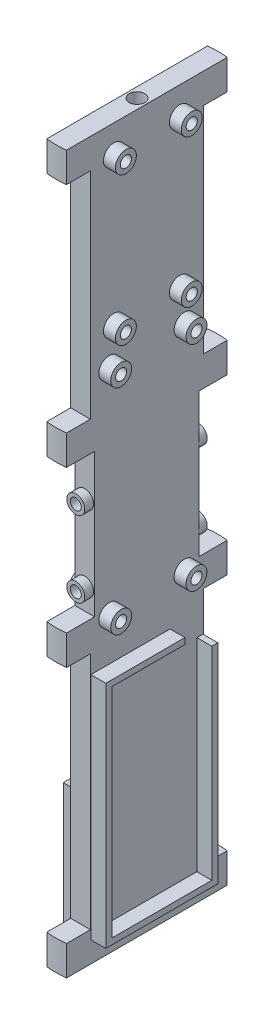
SolidWorks part; units mm, degrees
ref_plane "Front Plane" through (0, 0, 0) normal (0, 0, 1) x (1, 0, 0)
ref_plane "Top Plane" through (0, 0, 0) normal (0, 1, 0) x (1, 0, 0)
ref_plane "Right Plane" through (0, 0, 0) normal (1, 0, 0) x (0, 0, -1)
sketch "Sketch1" plane through (0, 0, 0) normal (0, 1, 0) x (1, 0, 0)
  line L2 (2.0955, -17.0804) -> (2.0955, 17.0804)
  line L4 (-2.0955, -17.0804) -> (-2.0955, 17.0804)
  line L5 (2.0955, -17.0804) -> (-2.0955, 17.0804) construction
  line L6 (2.0955, 17.0804) -> (-2.0955, -17.0804) construction
  circle A0 centre (0, 0) radius 17.4625 construction
  arc A1 (-2.0955, 17.0804) -> (2.0955, 17.0804) centre (0, 0) cw
  arc A2 (-2.0955, -17.0804) -> (2.0955, -17.0804) centre (0, 0) ccw
  circle A4 centre (0, 0) radius 1.651
  point P11 (0, 0)
  dimension "D1" = 34.925
  dimension "D2" = 4.191
  dimension "D3" = 0.254
  dimension "D5" = 3.302
extrude "Boss-Extrude1" add sketch "Sketch1" along normal blind 152.4
ref_plane "Plane1" through (0, 0, -17.2085) normal (0, 0, -1) x (-1, 0, 0)
sketch "Sketch2" plane through (0, 0, -17.2085) normal (0, 0, -1) x (-1, 0, 0)
  line L0 (-2.0955, 152.4) -> (-2.0955, 0) construction
  line L1 (-2.0955, 93.98) -> (2.0955, 93.98)
  line L2 (-2.0955, 93.98) -> (-2.0955, 63.5)
  line L3 (-2.0955, 63.5) -> (2.0955, 63.5)
  line L4 (2.0955, 93.98) -> (2.0955, 63.5)
  line L5 (2.0955, 152.4) -> (2.0955, 0) construction
  line L6 (0, 0) -> (0, 152.4) construction
  line L7 (2.0955, 152.4) -> (-2.0955, 152.4) construction
  point P6 (0, 76.2)
  dimension "D1" = 12.7
  dimension "D2" = 30.48
extrude "Cut-Extrude1" cut sketch "Sketch2" against normal blind 6.096
sketch "Sketch3" plane through (0, 0, -11.1125) normal (0, 0, -1) x (-1, 0, 0)
  line L0 (0, 63.5) -> (0, 93.98) construction
  line L1 (2.0955, 63.5) -> (-2.0955, 63.5) construction
  line L2 (-2.0955, 93.98) -> (2.0955, 93.98) construction
  line L3 (-2.0955, 63.5) -> (2.0955, 63.5) construction
  circle A0 centre (0, 68.0339) radius 1.905
  circle A1 centre (0, 84.1629) radius 1.905
  dimension "D1" = 3.81
  dimension "D3" = 16.129
  dimension "D4" = 4.5339
extrude "Boss-Extrude2" add sketch "Sketch3" along normal blind 1.905
sketch "Sketch4" plane through (0, 0, -13.0175) normal (0, 0, -1) x (-1, 0, 0)
  circle A0 centre (0, 84.1629) radius 1.1748
  circle A1 centre (0, 68.0339) radius 1.1748
  dimension "D1" = 2.3495
extrude "Cut-Extrude2" cut sketch "Sketch4" against normal blind 6.35
mirror "Mirror1" about plane through (0, 0, 0) normal (0, 0, 1) of "Cut-Extrude2", "Boss-Extrude2", "Cut-Extrude1"
sketch "Sketch5" plane through (-2.0955, 0, 0) normal (-1, 0, 0) x (0, 0, 1)
  line L0 (-17.0804, 152.4) -> (17.0804, 152.4) construction
  line L10 (8.385, 150.495) -> (8.385, 106.045)
  line L11 (8.385, 106.045) -> (10.29, 106.045)
  line L12 (10.29, 150.495) -> (10.29, 106.045)
  line L14 (-8.385, 150.495) -> (-8.385, 106.045)
  line L15 (-8.385, 106.045) -> (-10.29, 106.045)
  line L16 (-10.29, 150.495) -> (-10.29, 106.045)
  line L17 (-7.75, 149.86) -> (-7.75, 82.86) construction
  line L18 (7.75, 149.86) -> (7.75, 82.86) construction
  line L19 (-8.385, 150.495) -> (8.385, 150.495)
  line L20 (10.29, 150.495) -> (10.29, 152.4)
  line L21 (10.29, 152.4) -> (-10.29, 152.4)
  line L22 (-10.29, 152.4) -> (-10.29, 150.495)
  dimension "D1" = 46.355
  dimension "D2" = 1.905
  dimension "D3" = 1.905
  dimension "D4" = 0.635
  dimension "D5" = 0.635
extrude "2s LiPo Mounting Frame 550 mAh" [suppressed] add sketch "Sketch5" along normal blind 6.35
sketch "Sketch10" plane through (2.0955, 0, 0) normal (1, 0, 0) x (0, 0, -1)
  line L4 (10.405, 0.635) -> (10.405, 35.445)
  line L5 (10.405, 35.445) -> (-2.785, 35.445)
  line L6 (-10.405, 35.445) -> (-10.405, 0.635)
  line L7 (-10.405, 0.635) -> (10.405, 0.635)
  line L12 (9.135, 34.175) -> (-2.785, 34.175)
  line L13 (-9.135, 34.175) -> (-9.135, 1.905)
  line L14 (-9.135, 1.905) -> (9.135, 1.905)
  line L15 (9.135, 1.905) -> (9.135, 34.175)
  line L16 (-9.135, 34.175) -> (-9.135, 35.445)
  line L17 (-2.785, 34.175) -> (-2.785, 35.445)
  line L18 (-9.135, 35.445) -> (-10.405, 35.445)
  line L19 (10.405, 35.445) -> (-10.405, 35.445) construction
  line L20 (9.135, 34.175) -> (-9.135, 34.175) construction
  dimension "D3" = 6.35
  dimension "D2" = 1.27
extrude "1s Lipo Mounting Frame 550 mAh" [suppressed] add sketch "Sketch10" along normal blind 2.54
sketch "Sketch11" plane through (-2.0955, 0, 0) normal (-1, 0, 0) x (0, 0, 1)
  line L0 (-7.75, 149.86) -> (-7.75, 82.86) construction
  line L1 (-7.75, 82.225) -> (7.75, 82.225)
  line L2 (-7.75, 82.225) -> (-7.75, 80.32)
  line L3 (-7.75, 80.32) -> (7.75, 80.32)
  line L4 (7.75, 82.225) -> (7.75, 80.32)
  line L5 (7.75, 149.86) -> (7.75, 82.86) construction
  dimension "D1" = 0.635
  dimension "D2" = 1.905
extrude "2s LiPo Mounting Stop" [suppressed] add sketch "Sketch11" along normal blind 1.905
sketch "Sketch6" plane through (-2.0955, 0, 0) normal (-1, 0, 0) x (0, 0, 1)
  circle A0 centre (-3.1115, 52.5145) radius 2.2225
  arc A1 (11.049, 12.2555) -> (7.874, 12.2555) centre (9.4615, 12.2555) ccw construction
  arc A2 (-4.699, 52.5145) -> (-1.524, 52.5145) centre (-3.1115, 52.5145) ccw construction
  arc A3 (-1.524, 52.5145) -> (-4.699, 52.5145) centre (-3.1115, 52.5145) ccw construction
  arc A4 (11.049, 12.2555) -> (7.874, 12.2555) centre (9.4615, 12.2555) ccw construction
  arc A5 (-4.699, 52.5145) -> (-1.524, 52.5145) centre (-3.1115, 52.5145) ccw construction
  arc A6 (-1.524, 52.5145) -> (-4.699, 52.5145) centre (-3.1115, 52.5145) ccw construction
  arc A7 (7.874, 12.2555) -> (11.049, 12.2555) centre (9.4615, 12.2555) ccw construction
  arc A8 (7.874, 12.2555) -> (11.049, 12.2555) centre (9.4615, 12.2555) ccw construction
  circle A9 centre (-3.1115, 52.5145) radius 1.1811
  circle A10 centre (9.4615, 12.2555) radius 2.2225
  circle A11 centre (9.4615, 12.2555) radius 1.1811
  dimension "D1" = 2.3622
  dimension "D2" = 4.445
extrude "Eggfinder Mini Mounts 550 mAh" [suppressed] add sketch "Sketch6" along normal up to surface (4.064 mm away)
sketch "Sketch7" plane through (2.0955, 0, 0) normal (1, 0, 0) x (0, 0, -1)
  circle A0 centre (8.001, 107.823) radius 1.3716 construction
  circle A1 centre (-8.001, 107.823) radius 1.3716 construction
  circle A2 centre (-8.001, 62.357) radius 1.3716 construction
  circle A3 centre (8.001, 62.357) radius 1.3716 construction
  circle A4 centre (8.001, 107.823) radius 1.3716 construction
  circle A5 centre (-8.001, 107.823) radius 1.3716 construction
  circle A6 centre (-8.001, 62.357) radius 1.3716 construction
  circle A7 centre (8.001, 62.357) radius 1.3716 construction
  circle A8 centre (8.001, 62.357) radius 2.2225
  circle A9 centre (8.001, 62.357) radius 1.1811
  circle A10 centre (-8.001, 62.357) radius 2.2225
  circle A11 centre (-8.001, 62.357) radius 1.1811
  circle A12 centre (-8.001, 107.823) radius 2.2225
  circle A13 centre (-8.001, 107.823) radius 1.1811
  circle A14 centre (8.001, 107.823) radius 2.2225
  circle A15 centre (8.001, 107.823) radius 1.1811
  dimension "D1" = 2.3622
  dimension "D2" = 4.445
extrude "Stratologger Mounts" add sketch "Sketch7" along normal up to surface (2.54 mm away)
sketch "Sketch8" plane through (2.0955, 0, 0) normal (1, 0, 0) x (0, 0, -1)
  circle A0 centre (7, 146.51) radius 1.65 construction
  circle A1 centre (-7, 146.51) radius 1.65 construction
  circle A2 centre (-7, 115.11) radius 1.65 construction
  circle A3 centre (7, 115.11) radius 1.65 construction
  circle A4 centre (7, 146.51) radius 1.65 construction
  circle A5 centre (-7, 146.51) radius 1.65 construction
  circle A6 centre (-7, 115.11) radius 1.65 construction
  circle A7 centre (7, 115.11) radius 1.65 construction
  circle A8 centre (7, 115.11) radius 2.2225
  circle A9 centre (7, 115.11) radius 1.1811
  circle A10 centre (-7, 115.11) radius 2.2225
  circle A11 centre (-7, 115.11) radius 1.1811
  circle A12 centre (-7, 146.51) radius 1.1811
  circle A13 centre (-7, 146.51) radius 2.2225
  circle A14 centre (7, 146.51) radius 1.1811
  circle A15 centre (7, 146.51) radius 2.2225
  dimension "D1" = 2.3622
  dimension "D2" = 4.445
extrude "EasyMini Mounts" add sketch "Sketch8" along normal up to surface (2.54 mm away)
sketch "Sketch9" plane through (2.0955, 0, 0) normal (1, 0, 0) x (0, 0, -1)
  line L0 (-17.0804, 63.5) -> (-17.0804, 0) construction
  line L1 (19.6204, 6.35) -> (12.0004, 6.35)
  line L2 (19.6204, 6.35) -> (19.6204, 57.15)
  line L3 (19.6204, 57.15) -> (12.0004, 57.15)
  line L4 (12.0004, 6.35) -> (12.0004, 57.15)
  line L5 (-17.0804, 152.4) -> (-17.0804, 93.98) construction
  line L6 (-19.6204, 6.35) -> (-12.0004, 6.35)
  line L7 (-19.6204, 6.35) -> (-19.6204, 57.15)
  line L8 (-19.6204, 57.15) -> (-12.0004, 57.15)
  line L9 (-12.0004, 6.35) -> (-12.0004, 57.15)
  line L11 (-19.6204, 100.33) -> (-12.0004, 100.33)
  line L12 (-19.6204, 100.33) -> (-19.6204, 146.05)
  line L13 (-19.6204, 146.05) -> (-12.0004, 146.05)
  line L14 (-12.0004, 100.33) -> (-12.0004, 146.05)
  line L16 (19.6204, 100.33) -> (12.0004, 100.33)
  line L17 (19.6204, 100.33) -> (19.6204, 146.05)
  line L18 (19.6204, 146.05) -> (12.0004, 146.05)
  line L19 (12.0004, 100.33) -> (12.0004, 146.05)
  line L20 (-17.0804, 152.4) -> (17.0804, 152.4) construction
  line L21 (-11.1125, 93.98) -> (-17.0804, 93.98) construction
  line L22 (-11.1125, 63.5) -> (-17.0804, 63.5) construction
  line L23 (-17.0804, 0) -> (17.0804, 0) construction
  line L24 (17.0804, 63.5) -> (17.0804, 0) construction
  dimension "D1" = 5.08
  dimension "D2" = 6.35
  dimension "D3" = 6.35
  dimension "D4" = 6.35
  dimension "D5" = 6.35
  dimension "D6" = 2.54
  dimension "D7" = 2.54
  dimension "D8" = 2.54
extrude "Wire Passthroughs" cut sketch "Sketch9" against normal through all
sketch "Sketch12" plane through (-2.0955, 0, 0) normal (-1, 0, 0) x (0, 0, 1)
  arc A1 (-7.874, 103.9495) -> (-4.699, 103.9495) centre (-6.2865, 103.9495) ccw construction
  arc A2 (-4.699, 103.9495) -> (-7.874, 103.9495) centre (-6.2865, 103.9495) ccw construction
  arc A3 (4.699, 63.6905) -> (7.874, 63.6905) centre (6.2865, 63.6905) ccw construction
  arc A4 (7.874, 63.6905) -> (4.699, 63.6905) centre (6.2865, 63.6905) ccw construction
  arc A5 (-7.874, 103.9495) -> (-4.699, 103.9495) centre (-6.2865, 103.9495) ccw construction
  arc A6 (-4.699, 103.9495) -> (-7.874, 103.9495) centre (-6.2865, 103.9495) ccw construction
  arc A7 (4.699, 63.6905) -> (7.874, 63.6905) centre (6.2865, 63.6905) ccw construction
  arc A8 (7.874, 63.6905) -> (4.699, 63.6905) centre (6.2865, 63.6905) ccw construction
  circle A9 centre (-6.2865, 103.9495) radius 2.2225
  circle A10 centre (-6.2865, 103.9495) radius 1.1811
  circle A11 centre (6.2865, 63.6905) radius 2.2225
  circle A12 centre (6.2865, 63.6905) radius 1.1811
  dimension "D2" = 2.3622
  dimension "D3" = 4.445
extrude "Eggfinder Mini Mounts Small 2s" add sketch "Sketch12" along normal up to surface (3.81 mm away)
sketch "Sketch13" plane through (-2.0955, 0, 0) normal (-1, 0, 0) x (0, 0, 1)
  line L8 (-9.1341, 1.905) -> (9.1341, 1.905)
  line L9 (9.1341, 1.905) -> (9.1341, 27.675)
  line L10 (9.1341, 27.675) -> (-9.1341, 27.675)
  line L11 (-9.1341, 27.675) -> (-9.1341, 1.905)
  line L12 (-9.1341, 1.905) -> (9.1341, 1.905)
  line L13 (9.1341, 1.905) -> (9.1341, 27.675)
  line L14 (9.1341, 27.675) -> (-5.3241, 27.675)
  line L15 (-9.1341, 24.5) -> (-9.1341, 1.905)
  line L16 (-9.1341, 24.5) -> (-10.4041, 24.5)
  line L17 (-5.3241, 27.675) -> (-5.3241, 28.945)
  line L18 (-8.4991, 27.04) -> (8.4991, 27.04) construction
  line L19 (-8.4991, 27.04) -> (-8.4991, 2.54) construction
  line L20 (-10.4041, 0.635) -> (10.4041, 0.635)
  line L21 (10.4041, 0.635) -> (10.4041, 28.945)
  line L22 (10.4041, 28.945) -> (-10.4041, 28.945)
  line L23 (-10.4041, 28.945) -> (-10.4041, 0.635)
  line L24 (-10.4041, 0.635) -> (10.4041, 0.635)
  line L25 (10.4041, 0.635) -> (10.4041, 28.945)
  line L26 (10.4041, 28.945) -> (-5.3241, 28.945)
  line L27 (-10.4041, 24.5) -> (-10.4041, 0.635)
  dimension "D3" = 2.54
  dimension "D4" = 3.175
  dimension "D1" = 0.635
  dimension "D2" = 1.905
extrude "1s LiPo Mouints Small 2s" add sketch "Sketch13" along normal blind 3.175
sketch "Sketch14" plane through (2.0955, 0, 0) normal (1, 0, 0) x (0, 0, -1)
  line L8 (-10.635, 5.715) -> (10.635, 5.715)
  line L9 (10.635, 5.715) -> (10.635, 51.985)
  line L10 (10.635, 51.985) -> (-10.635, 51.985)
  line L11 (-10.635, 51.985) -> (-10.635, 5.715)
  line L12 (-10.635, 5.715) -> (10.635, 5.715)
  line L13 (10.635, 5.715) -> (10.635, 48.81)
  line L14 (4.92, 51.985) -> (-10.635, 51.985)
  line L15 (-10.635, 51.985) -> (-10.635, 5.715)
  line L16 (11.905, 48.81) -> (10.635, 48.81)
  line L17 (4.92, 51.985) -> (4.92, 53.255)
  line L18 (10, 51.35) -> (10, 6.35) construction
  line L19 (-10, 51.35) -> (10, 51.35) construction
  line L20 (-11.905, 4.445) -> (11.905, 4.445)
  line L21 (11.905, 4.445) -> (11.905, 53.255)
  line L22 (11.905, 53.255) -> (-11.905, 53.255)
  line L23 (-11.905, 53.255) -> (-11.905, 4.445)
  line L24 (-11.905, 4.445) -> (11.905, 4.445)
  line L25 (11.905, 4.445) -> (11.905, 48.81)
  line L26 (4.92, 53.255) -> (-11.905, 53.255)
  line L27 (-11.905, 53.255) -> (-11.905, 4.445)
  dimension "D3" = 5.08
  dimension "D4" = 2.54
  dimension "D1" = 0.635
  dimension "D2" = 1.905
extrude "Boss-Extrude5" add sketch "Sketch14" along normal blind 3.175
